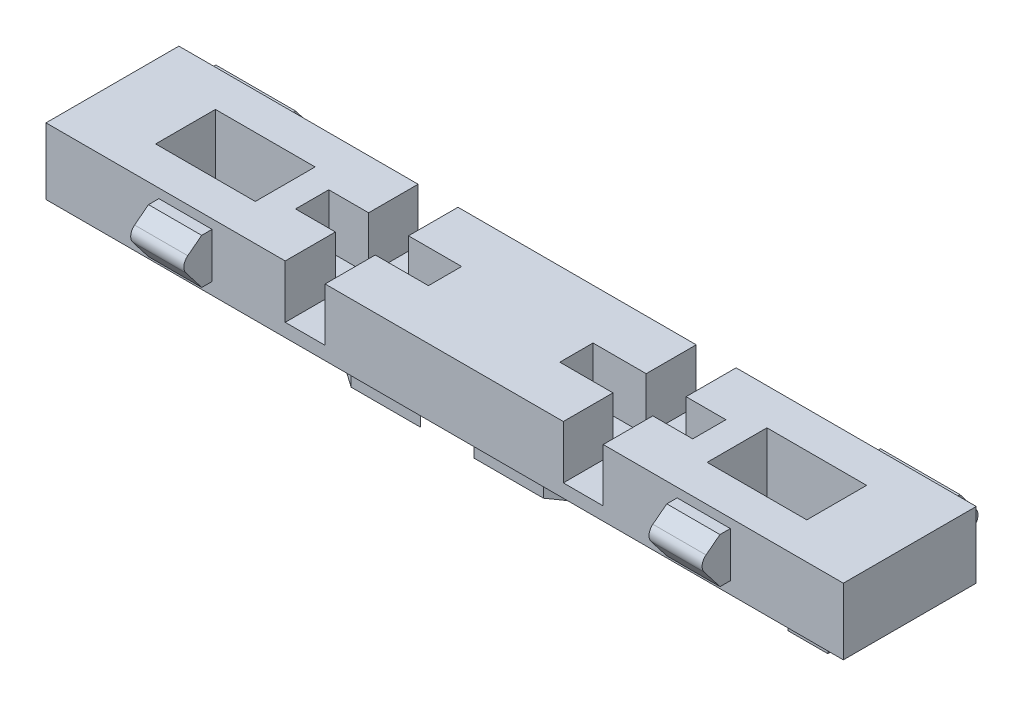
SolidWorks part; units mm, degrees
ref_plane "Front Plane" through (0, 0, 0) normal (0, 0, 1) x (1, 0, 0)
ref_plane "Top Plane" through (0, 0, 0) normal (0, 1, 0) x (1, 0, 0)
ref_plane "Right Plane" through (0, 0, 0) normal (1, 0, 0) x (0, 0, -1)
sketch "Sketch2" plane through (0, 0, 0) normal (0, 1, 0) x (1, 0, 0)
  line L0 (-30, 5) -> (30, 5)
  line L1 (-30, 5) -> (-30, -5)
  line L2 (-30, -5) -> (30, -5)
  line L3 (30, 5) -> (30, -5)
  line L4 (-30, 5) -> (30, -5) construction
  line L5 (-30, -5) -> (30, 5) construction
  line L6 (-24.5, 2.25) -> (-17, 2.25)
  line L7 (-24.5, 2.25) -> (-24.5, -2.25)
  line L8 (-24.5, -2.25) -> (-17, -2.25)
  line L9 (-17, 2.25) -> (-17, -2.25)
  line L10 (-24.5, 2.25) -> (-17, -2.25) construction
  line L11 (-24.5, -2.25) -> (-17, 2.25) construction
  line L12 (17, 2.25) -> (24.5, 2.25)
  line L13 (17, 2.25) -> (17, -2.25)
  line L14 (17, -2.25) -> (24.5, -2.25)
  line L15 (24.5, 2.25) -> (24.5, -2.25)
  line L16 (17, 2.25) -> (24.5, -2.25) construction
  line L17 (17, -2.25) -> (24.5, 2.25) construction
  point P4 (0, 0)
  point P9 (-20.75, 0)
  point P14 (20.75, 0)
extrude "Boss-Extrude2" add sketch "Sketch2" along normal blind 5
ref_plane "Plane1" through (0, 0, 0) normal (0, 0.7071, -0.7071) x (-1, 0, 0)
sketch "Sketch6" plane through (30, 0, 0) normal (1, 0, 0) x (0, 0, -1)
  line L6 (-5.0057, 0.9118) -> (-5.0057, 4.3118)
  line L7 (-5.7787, 0.9118) -> (-5.0057, 0.9118)
  line L8 (-6.9702, 2.4531) -> (-5.7787, 0.9118)
  line L9 (-5.7862, 4.3118) -> (-6.8339, 3.5064)
  line L10 (-5.0057, 4.3118) -> (-5.7862, 4.3118)
  line L17 (-5, 5) -> (-5, 0) construction
  line L18 (5, 5) -> (5, 0) construction
  line L20 (5.7854, 4.3755) -> (5.0123, 4.3755)
  line L21 (6.9768, 2.8342) -> (5.7854, 4.3755)
  line L22 (5.7928, 0.9755) -> (6.8406, 1.7809)
  line L23 (5.0123, 0.9755) -> (5.7928, 0.9755)
  line L24 (5.0123, 4.3755) -> (5.0123, 0.9755)
  arc A1 (-6.8339, 3.5064) -> (-6.9702, 2.4531) centre (-6.3769, 2.9118) ccw
  arc A3 (6.8406, 1.7809) -> (6.9768, 2.8342) centre (6.3835, 2.3755) ccw
extrude "Boss-Extrude5" add sketch "Sketch6" against normal blind 60 separate body
sketch "Sketch7" plane through (0, 0, -5) normal (0, 0, -1) x (-1, 0, 0)
  line L0 (-30, 0) -> (30, 0) construction
  line L1 (-30, 5) -> (-28, 5)
  line L2 (-30, 5) -> (-30, 0)
  line L3 (-30, 0) -> (-28, 0)
  line L4 (-28, 5) -> (-28, 0)
  line L5 (-30, 5) -> (-28, 0) construction
  line L6 (-30, 0) -> (-28, 5) construction
  line L7 (-28, 5) -> (-22, 5) construction
  line L8 (-30, 5) -> (30, 5) construction
  line L9 (22, 5) -> (28, 5) construction
  line L10 (-22, 5) -> (22, 5)
  line L11 (-22, 5) -> (-22, 0)
  line L12 (-22, 0) -> (22, 0)
  line L13 (22, 5) -> (22, 0)
  line L14 (-22, 5) -> (22, 0) construction
  line L15 (-22, 0) -> (22, 5) construction
  line L17 (28, 5) -> (30, 5)
  line L18 (28, 5) -> (28, 0)
  line L19 (28, 0) -> (30, 0)
  line L20 (30, 5) -> (30, 0)
  line L21 (28, 5) -> (30, 0) construction
  line L22 (28, 0) -> (30, 5) construction
  point P4 (-29, 2.5)
  point P15 (0, 2.5)
  point P20 (29, 2.5)
extrude "Cut-Extrude1" cut sketch "Sketch7" along normal blind 13
sketch "Sketch8" plane through (0, 0, 5) normal (0, 0, 1) x (1, 0, 0)
  line L0 (-30, 0) -> (30, 0) construction
  line L1 (30, 5) -> (21.5, 5)
  line L2 (30, 5) -> (30, 0)
  line L3 (30, 0) -> (21.5, 0)
  line L4 (21.5, 5) -> (21.5, 0)
  line L5 (30, 5) -> (21.5, 0) construction
  line L6 (30, 0) -> (21.5, 5) construction
  line L7 (21.5, 5) -> (17.5, 5) construction
  line L8 (-30, 5) -> (30, 5) construction
  line L9 (-17.5, 5) -> (-21.5, 5) construction
  line L10 (17.5, 5) -> (-17.5, 5)
  line L11 (17.5, 5) -> (17.5, 0)
  line L12 (17.5, 0) -> (-17.5, 0)
  line L13 (-17.5, 5) -> (-17.5, 0)
  line L14 (17.5, 5) -> (-17.5, 0) construction
  line L15 (17.5, 0) -> (-17.5, 5) construction
  line L17 (-21.5, 5) -> (-30, 5)
  line L18 (-21.5, 5) -> (-21.5, 0)
  line L19 (-21.5, 0) -> (-30, 0)
  line L20 (-30, 5) -> (-30, 0)
  line L21 (-21.5, 5) -> (-30, 0) construction
  line L22 (-21.5, 0) -> (-30, 5) construction
  point P4 (25.75, 2.5)
  point P14 (0, 2.5)
  point P19 (-25.75, 2.5)
extrude "Cut-Extrude2" cut sketch "Sketch8" along normal blind 13
sketch "Sketch9" plane through (0, 5, 0) normal (0, 1, 0) x (1, 0, 0)
  line L0 (11.929, 5.2237) -> (8.929, 5.2237)
  line L1 (8.929, 5.2237) -> (8.929, 1.2348)
  line L2 (8.929, 1.2348) -> (4.929, 1.2348)
  line L3 (4.929, 1.2348) -> (4.929, -1.2652)
  line L4 (4.929, -1.2652) -> (8.929, -1.2652)
  line L5 (8.929, -1.2652) -> (8.929, -5.0152)
  line L6 (8.929, -5.0152) -> (11.929, -5.0152)
  line L7 (11.929, -5.0152) -> (11.929, -1.2652)
  line L8 (11.929, -1.2652) -> (14.929, -1.2652)
  line L9 (14.929, -1.2652) -> (14.929, 1.2348)
  line L10 (14.929, 1.2348) -> (11.929, 1.2348)
  line L11 (11.929, 1.2348) -> (11.929, 5.2237)
  line L12 (11.929, 5.2237) -> (29.929, 5.2237) construction
extrude "Cut-Extrude3" cut sketch "Sketch9" against normal blind 4
sketch "Sketch10" plane through (0, 5, 0) normal (0, 1, 0) x (1, 0, 0)
  line L0 (-8.9989, 5.544) -> (-11.9989, 5.544)
  line L1 (-11.9989, 5.544) -> (-11.9989, 1.2761)
  line L2 (-11.9989, 1.2761) -> (-14.9989, 1.2761)
  line L3 (-14.9989, 1.2761) -> (-14.9989, -1.2239)
  line L4 (-14.9989, -1.2239) -> (-11.9989, -1.2239)
  line L5 (-11.9989, -1.2239) -> (-11.9989, -5.4573)
  line L6 (-11.9989, -5.4573) -> (-8.9989, -5.4573)
  line L7 (-8.9989, -5.4573) -> (-8.9989, -1.2239)
  line L8 (-8.9989, -1.2239) -> (-4.9989, -1.2239)
  line L9 (-4.9989, -1.2239) -> (-4.9989, 1.2761)
  line L10 (-4.9989, 1.2761) -> (-8.9989, 1.2761)
  line L11 (-8.9989, 1.2761) -> (-8.9989, 5.544)
  line L12 (-11.9989, 5.544) -> (-29.9989, 5.544) construction
extrude "Cut-Extrude4" cut sketch "Sketch10" against normal blind 4
sketch "Sketch11" plane through (0, 0, 0) normal (0, -1, 0) x (1, 0, 0)
  line L0 (-17.0578, 2.3059) -> (-12.6053, 1.0266)
  line L1 (-27.2356, 3.8469) -> (-24.628, 3.8469)
  line L2 (-27.2356, 3.8469) -> (-27.2356, 1.2393)
  line L3 (-27.2356, 1.2393) -> (-24.628, 1.2393)
  line L4 (-24.628, 3.8469) -> (-24.628, 1.2393)
  line L5 (-27.2356, 3.8469) -> (-24.628, 1.2393) construction
  line L6 (-27.2356, 1.2393) -> (-24.628, 3.8469) construction
  line L7 (-12.6053, 1.0266) -> (-7.2891, 4.748)
  line L8 (-7.2891, 4.748) -> (-2.0578, 4.748)
  line L9 (-2.0578, 4.748) -> (-12.0578, -2.252)
  line L10 (-12.0578, -2.252) -> (-17.0578, -1.002)
  line L11 (-17.0578, -1.002) -> (-17.0578, 2.3059)
  line L12 (11.9422, -2.252) -> (16.9422, -0.8155)
  line L13 (16.9422, -0.8155) -> (16.9422, 2.3059)
  line L14 (16.9422, 2.3059) -> (12.4898, 1.0266)
  line L15 (12.4898, 1.0266) -> (7.1736, 4.748)
  line L16 (7.1736, 4.748) -> (1.9422, 4.748)
  line L17 (1.9422, 4.748) -> (11.9422, -2.252)
  line L18 (28.0093, 4.1809) -> (25.0093, 4.1809)
  line L19 (28.0093, 4.1809) -> (28.0093, 1.1809)
  line L20 (28.0093, 1.1809) -> (25.0093, 1.1809)
  line L21 (25.0093, 4.1809) -> (25.0093, 1.1809)
  line L22 (28.0093, 4.1809) -> (25.0093, 1.1809) construction
  line L23 (28.0093, 1.1809) -> (25.0093, 4.1809) construction
  point P4 (-25.9318, 2.5431)
  point P21 (26.5093, 2.6809)
extrude "Boss-Extrude6" add sketch "Sketch11" along normal blind 1
